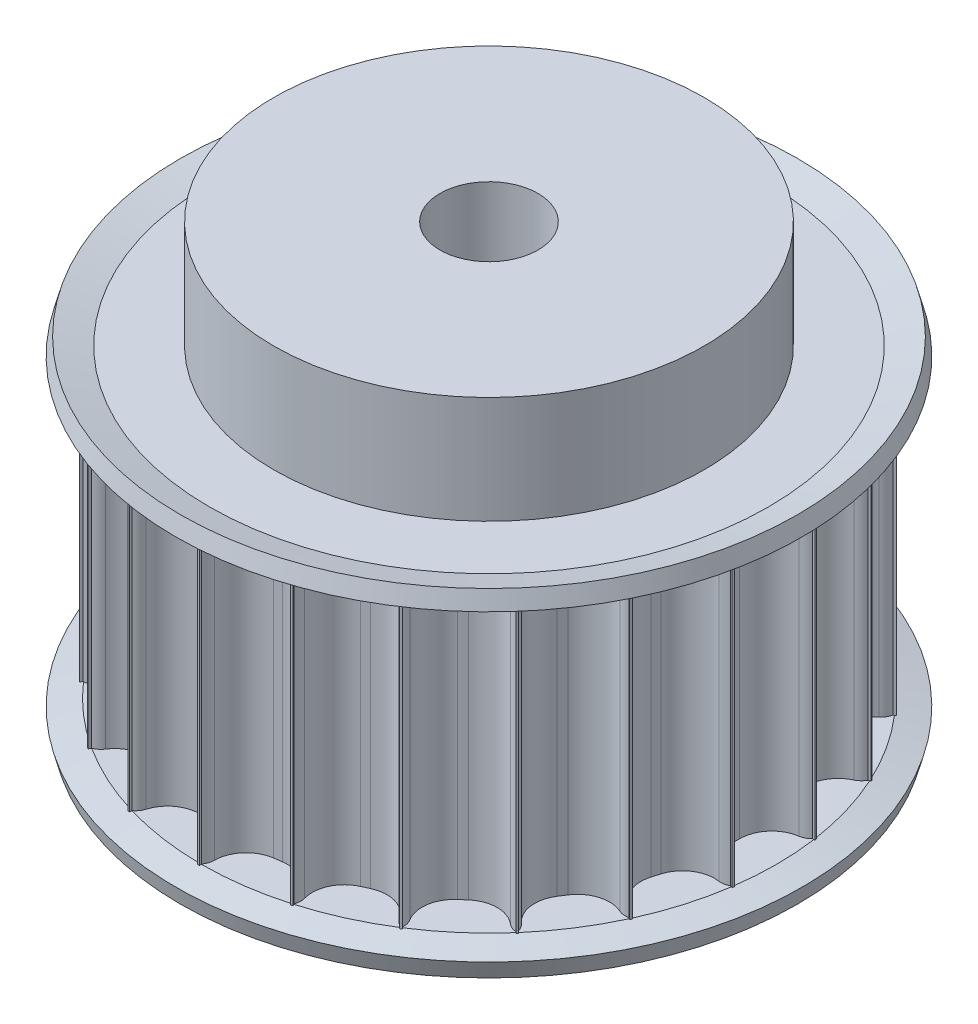
SolidWorks part; units mm, degrees
ref_plane "Front Plane" through (0, 0, 0) normal (0, 0, 1) x (1, 0, 0)
ref_plane "Top Plane" through (0, 0, 0) normal (0, 1, 0) x (1, 0, 0)
ref_plane "Right Plane" through (0, 0, 0) normal (1, 0, 0) x (0, 0, -1)
sketch "Sketch1" plane through (0, 0, 0) normal (0, 1, 0) x (1, 0, 0)
  circle A0 centre (0, 0) radius 6
  circle A1 centre (0, 0) radius 27
  dimension "D1" = 12
  dimension "D2" = 54
extrude "Boss-Extrude1" add sketch "Sketch1" along normal blind 27
sketch "Sketch2" plane through (0, 27, 0) normal (0, 1, 0) x (1, 0, 0)
  line L0 (0, 0) -> (31.3438, 0) construction
  line L1 (23.1111, 0.3611) -> (23.1111, -0.3611)
  line L2 (26.5, 3.75) -> (27.8859, 3.75)
  line L3 (27.8859, 3.75) -> (27.8859, -3.75)
  line L4 (27.8859, -3.75) -> (26.5, -3.75)
  line L5 (22.2766, -6.1647) -> (22.0732, -6.8576)
  line L6 (26.4831, -3.8678) -> (27.8128, -4.2583)
  line L7 (27.8128, -4.2583) -> (25.6998, -11.4545)
  line L8 (25.6998, -11.4545) -> (24.3701, -11.064)
  line L9 (19.6375, -12.191) -> (19.2471, -12.7986)
  line L10 (24.3206, -11.1723) -> (25.4865, -11.9215)
  line L11 (25.4865, -11.9215) -> (21.4317, -18.2309)
  line L12 (21.4317, -18.2309) -> (20.2658, -17.4817)
  line L13 (15.4074, -17.2297) -> (14.8617, -17.7026)
  line L14 (20.1879, -17.5716) -> (21.0954, -18.619)
  line L15 (21.0954, -18.619) -> (15.4273, -23.5305)
  line L16 (15.4273, -23.5305) -> (14.5197, -22.4831)
  line L17 (9.9291, -20.8726) -> (9.2722, -21.1726)
  line L18 (14.4196, -22.5474) -> (14.9953, -23.8081)
  line L19 (14.9953, -23.8081) -> (8.1731, -26.9237)
  line L20 (8.1731, -26.9237) -> (7.5974, -25.6631)
  line L21 (3.6465, -22.8245) -> (2.9316, -22.9272)
  line L22 (7.4832, -25.6966) -> (7.6804, -27.0683)
  line L23 (7.6804, -27.0683) -> (0.2567, -28.1357)
  line L24 (0.2567, -28.1357) -> (0.0595, -26.7639)
  line L25 (-2.9316, -22.9272) -> (-3.6465, -22.8245)
  line L26 (-0.0595, -26.7639) -> (-0.2567, -28.1357)
  line L27 (-0.2567, -28.1357) -> (-7.6804, -27.0683)
  line L28 (-7.6804, -27.0683) -> (-7.4832, -25.6966)
  line L29 (-9.2722, -21.1726) -> (-9.9291, -20.8726)
  line L30 (-7.5974, -25.6631) -> (-8.1731, -26.9237)
  line L31 (-8.1731, -26.9237) -> (-14.9953, -23.8081)
  line L32 (-14.9953, -23.8081) -> (-14.4196, -22.5474)
  line L33 (-14.8617, -17.7026) -> (-15.4074, -17.2297)
  line L34 (-14.5197, -22.4831) -> (-15.4273, -23.5305)
  line L35 (-15.4273, -23.5305) -> (-21.0954, -18.619)
  line L36 (-21.0954, -18.619) -> (-20.1879, -17.5716)
  line L37 (-19.2471, -12.7986) -> (-19.6375, -12.191)
  line L38 (-20.2658, -17.4817) -> (-21.4317, -18.2309)
  line L39 (-21.4317, -18.2309) -> (-25.4865, -11.9215)
  line L40 (-25.4865, -11.9215) -> (-24.3206, -11.1723)
  line L41 (-22.0732, -6.8576) -> (-22.2766, -6.1647)
  line L42 (-24.3701, -11.064) -> (-25.6998, -11.4545)
  line L43 (-25.6998, -11.4545) -> (-27.8128, -4.2583)
  line L44 (-27.8128, -4.2583) -> (-26.4831, -3.8678)
  line L45 (-23.1111, -0.3611) -> (-23.1111, 0.3611)
  line L46 (-26.5, -3.75) -> (-27.8859, -3.75)
  line L47 (-27.8859, -3.75) -> (-27.8859, 3.75)
  line L48 (-27.8859, 3.75) -> (-26.5, 3.75)
  line L49 (-22.2766, 6.1647) -> (-22.0732, 6.8576)
  line L50 (-26.4831, 3.8678) -> (-27.8128, 4.2583)
  line L51 (-27.8128, 4.2583) -> (-25.6998, 11.4545)
  line L52 (-25.6998, 11.4545) -> (-24.3701, 11.064)
  line L53 (-19.6375, 12.191) -> (-19.2471, 12.7986)
  line L54 (-24.3206, 11.1723) -> (-25.4865, 11.9215)
  line L55 (-25.4865, 11.9215) -> (-21.4317, 18.2309)
  line L56 (-21.4317, 18.2309) -> (-20.2658, 17.4817)
  line L57 (-15.4074, 17.2297) -> (-14.8617, 17.7026)
  line L58 (-20.1879, 17.5716) -> (-21.0954, 18.619)
  line L59 (-21.0954, 18.619) -> (-15.4273, 23.5305)
  line L60 (-15.4273, 23.5305) -> (-14.5197, 22.4831)
  line L61 (-9.9291, 20.8726) -> (-9.2722, 21.1726)
  line L62 (-14.4196, 22.5474) -> (-14.9953, 23.8081)
  line L63 (-14.9953, 23.8081) -> (-8.1731, 26.9237)
  line L64 (-8.1731, 26.9237) -> (-7.5974, 25.6631)
  line L65 (-3.6465, 22.8245) -> (-2.9316, 22.9272)
  line L66 (-7.4832, 25.6966) -> (-7.6804, 27.0683)
  line L67 (-7.6804, 27.0683) -> (-0.2567, 28.1357)
  line L68 (-0.2567, 28.1357) -> (-0.0595, 26.7639)
  line L69 (2.9316, 22.9272) -> (3.6465, 22.8245)
  line L70 (0.0595, 26.7639) -> (0.2567, 28.1357)
  line L71 (0.2567, 28.1357) -> (7.6804, 27.0683)
  line L72 (7.6804, 27.0683) -> (7.4832, 25.6966)
  line L73 (9.2722, 21.1726) -> (9.9291, 20.8726)
  line L74 (7.5974, 25.6631) -> (8.1731, 26.9237)
  line L75 (8.1731, 26.9237) -> (14.9953, 23.8081)
  line L76 (14.9953, 23.8081) -> (14.4196, 22.5474)
  line L77 (14.8617, 17.7026) -> (15.4074, 17.2297)
  line L78 (14.5197, 22.4831) -> (15.4273, 23.5305)
  line L79 (15.4273, 23.5305) -> (21.0954, 18.619)
  line L80 (21.0954, 18.619) -> (20.1879, 17.5716)
  line L81 (19.2471, 12.7986) -> (19.6375, 12.191)
  line L82 (20.2658, 17.4817) -> (21.4317, 18.2309)
  line L83 (21.4317, 18.2309) -> (25.4865, 11.9215)
  line L84 (25.4865, 11.9215) -> (24.3206, 11.1723)
  line L85 (22.0732, 6.8576) -> (22.2766, 6.1647)
  line L86 (24.3701, 11.064) -> (25.6998, 11.4545)
  line L87 (25.6998, 11.4545) -> (27.8128, 4.2583)
  line L88 (27.8128, 4.2583) -> (26.4831, 3.8678)
  arc A0 (26.5, 3.75) -> (25.6633, 3.3275) centre (25.4393, 4.8107) cw
  arc A1 (25.6633, -3.3275) -> (23.1111, -0.3611) centre (26.1111, -0.3611) cw
  arc A2 (25.6633, 3.3275) -> (23.1111, 0.3611) centre (26.1111, 0.3611) ccw
  arc A3 (26.5, -3.75) -> (25.6633, -3.3275) centre (25.4393, -4.8107) ccw
  arc A4 (26.4831, -3.8678) -> (25.5612, -4.0375) centre (25.7642, -2.5513) cw
  arc A5 (23.6863, -10.4229) -> (22.0732, -6.8576) centre (24.9517, -7.7028) cw
  arc A6 (25.5612, -4.0375) -> (22.2766, -6.1647) centre (25.1551, -7.0099) ccw
  arc A7 (24.3701, -11.064) -> (23.6863, -10.4229) centre (23.0535, -11.7829) ccw
  arc A8 (24.3206, -11.1723) -> (23.3883, -11.0754) centre (24.0018, -9.7066) cw
  arc A9 (19.7903, -16.6738) -> (19.2471, -12.7986) centre (21.7708, -14.4205) cw
  arc A10 (23.3883, -11.0754) -> (19.6375, -12.191) centre (22.1613, -13.813) ccw
  arc A11 (20.2658, -17.4817) -> (19.7903, -16.6738) centre (18.8001, -17.8005) ccw
  arc A12 (20.1879, -17.5716) -> (19.3206, -17.216) centre (20.2949, -16.0755) cw
  arc A13 (14.2911, -21.574) -> (14.8617, -17.7026) centre (16.8262, -19.9699) cw
  arc A14 (19.3206, -17.216) -> (15.4074, -17.2297) centre (17.372, -19.497) ccw
  arc A15 (14.5197, -22.4831) -> (14.2911, -21.574) centre (13.0236, -22.3761) ccw
  arc A16 (14.4196, -22.5474) -> (13.6877, -21.9618) centre (14.9438, -21.142) cw
  arc A17 (7.6341, -24.7264) -> (9.2722, -21.1726) centre (10.5185, -23.9015) cw
  arc A18 (13.6877, -21.9618) -> (9.9291, -20.8726) centre (11.1754, -23.6015) ccw
  arc A19 (7.5974, -25.6631) -> (7.6341, -24.7264) centre (6.192, -25.1389) ccw
  arc A20 (7.4832, -25.6966) -> (6.9459, -24.9285) centre (8.3821, -24.4958) cw
  arc A21 (0.3587, -25.8756) -> (2.9316, -22.9272) centre (3.3586, -25.8967) cw
  arc A22 (6.9459, -24.9285) -> (3.6465, -22.8245) centre (4.0734, -25.7939) ccw
  arc A23 (0.0595, -26.7639) -> (0.3587, -25.8756) centre (-1.1413, -25.865) ccw
  arc A24 (-0.0595, -26.7639) -> (-0.3587, -25.8756) centre (1.1413, -25.865) cw
  arc A25 (-6.9459, -24.9285) -> (-3.6465, -22.8245) centre (-4.0734, -25.7939) cw
  arc A26 (-0.3587, -25.8756) -> (-2.9316, -22.9272) centre (-3.3586, -25.8967) ccw
  arc A27 (-7.4832, -25.6966) -> (-6.9459, -24.9285) centre (-8.3821, -24.4958) ccw
  arc A28 (-7.5974, -25.6631) -> (-7.6341, -24.7264) centre (-6.192, -25.1389) cw
  arc A29 (-13.6877, -21.9618) -> (-9.9291, -20.8726) centre (-11.1754, -23.6015) cw
  arc A30 (-7.6341, -24.7264) -> (-9.2722, -21.1726) centre (-10.5185, -23.9015) ccw
  arc A31 (-14.4196, -22.5474) -> (-13.6877, -21.9618) centre (-14.9438, -21.142) ccw
  arc A32 (-14.5197, -22.4831) -> (-14.2911, -21.574) centre (-13.0236, -22.3761) cw
  arc A33 (-19.3206, -17.216) -> (-15.4074, -17.2297) centre (-17.372, -19.497) cw
  arc A34 (-14.2911, -21.574) -> (-14.8617, -17.7026) centre (-16.8262, -19.9699) ccw
  arc A35 (-20.1879, -17.5716) -> (-19.3206, -17.216) centre (-20.2949, -16.0755) ccw
  arc A36 (-20.2658, -17.4817) -> (-19.7903, -16.6738) centre (-18.8001, -17.8005) cw
  arc A37 (-23.3883, -11.0754) -> (-19.6375, -12.191) centre (-22.1613, -13.813) cw
  arc A38 (-19.7903, -16.6738) -> (-19.2471, -12.7986) centre (-21.7708, -14.4205) ccw
  arc A39 (-24.3206, -11.1723) -> (-23.3883, -11.0754) centre (-24.0018, -9.7066) ccw
  arc A40 (-24.3701, -11.064) -> (-23.6863, -10.4229) centre (-23.0535, -11.7829) cw
  arc A41 (-25.5612, -4.0375) -> (-22.2766, -6.1647) centre (-25.1551, -7.0099) cw
  arc A42 (-23.6863, -10.4229) -> (-22.0732, -6.8576) centre (-24.9517, -7.7028) ccw
  arc A43 (-26.4831, -3.8678) -> (-25.5612, -4.0375) centre (-25.7642, -2.5513) ccw
  arc A44 (-26.5, -3.75) -> (-25.6633, -3.3275) centre (-25.4393, -4.8107) cw
  arc A45 (-25.6633, 3.3275) -> (-23.1111, 0.3611) centre (-26.1111, 0.3611) cw
  arc A46 (-25.6633, -3.3275) -> (-23.1111, -0.3611) centre (-26.1111, -0.3611) ccw
  arc A47 (-26.5, 3.75) -> (-25.6633, 3.3275) centre (-25.4393, 4.8107) ccw
  arc A48 (-26.4831, 3.8678) -> (-25.5612, 4.0375) centre (-25.7642, 2.5513) cw
  arc A49 (-23.6863, 10.4229) -> (-22.0732, 6.8576) centre (-24.9517, 7.7028) cw
  arc A50 (-25.5612, 4.0375) -> (-22.2766, 6.1647) centre (-25.1551, 7.0099) ccw
  arc A51 (-24.3701, 11.064) -> (-23.6863, 10.4229) centre (-23.0535, 11.7829) ccw
  arc A52 (-24.3206, 11.1723) -> (-23.3883, 11.0754) centre (-24.0018, 9.7066) cw
  arc A53 (-19.7903, 16.6738) -> (-19.2471, 12.7986) centre (-21.7708, 14.4205) cw
  arc A54 (-23.3883, 11.0754) -> (-19.6375, 12.191) centre (-22.1613, 13.813) ccw
  arc A55 (-20.2658, 17.4817) -> (-19.7903, 16.6738) centre (-18.8001, 17.8005) ccw
  arc A56 (-20.1879, 17.5716) -> (-19.3206, 17.216) centre (-20.2949, 16.0755) cw
  arc A57 (-14.2911, 21.574) -> (-14.8617, 17.7026) centre (-16.8262, 19.9699) cw
  arc A58 (-19.3206, 17.216) -> (-15.4074, 17.2297) centre (-17.372, 19.497) ccw
  arc A59 (-14.5197, 22.4831) -> (-14.2911, 21.574) centre (-13.0236, 22.3761) ccw
  arc A60 (-14.4196, 22.5474) -> (-13.6877, 21.9618) centre (-14.9438, 21.142) cw
  arc A61 (-7.6341, 24.7264) -> (-9.2722, 21.1726) centre (-10.5185, 23.9015) cw
  arc A62 (-13.6877, 21.9618) -> (-9.9291, 20.8726) centre (-11.1754, 23.6015) ccw
  arc A63 (-7.5974, 25.6631) -> (-7.6341, 24.7264) centre (-6.192, 25.1389) ccw
  arc A64 (-7.4832, 25.6966) -> (-6.9459, 24.9285) centre (-8.3821, 24.4958) cw
  arc A65 (-0.3587, 25.8756) -> (-2.9316, 22.9272) centre (-3.3586, 25.8967) cw
  arc A66 (-6.9459, 24.9285) -> (-3.6465, 22.8245) centre (-4.0734, 25.7939) ccw
  arc A67 (-0.0595, 26.7639) -> (-0.3587, 25.8756) centre (1.1413, 25.865) ccw
  arc A68 (0.0595, 26.7639) -> (0.3587, 25.8756) centre (-1.1413, 25.865) cw
  arc A69 (6.9459, 24.9285) -> (3.6465, 22.8245) centre (4.0734, 25.7939) cw
  arc A70 (0.3587, 25.8756) -> (2.9316, 22.9272) centre (3.3586, 25.8967) ccw
  arc A71 (7.4832, 25.6966) -> (6.9459, 24.9285) centre (8.3821, 24.4958) ccw
  arc A72 (7.5974, 25.6631) -> (7.6341, 24.7264) centre (6.192, 25.1389) cw
  arc A73 (13.6877, 21.9618) -> (9.9291, 20.8726) centre (11.1754, 23.6015) cw
  arc A74 (7.6341, 24.7264) -> (9.2722, 21.1726) centre (10.5185, 23.9015) ccw
  arc A75 (14.4196, 22.5474) -> (13.6877, 21.9618) centre (14.9438, 21.142) ccw
  arc A76 (14.5197, 22.4831) -> (14.2911, 21.574) centre (13.0236, 22.3761) cw
  arc A77 (19.3206, 17.216) -> (15.4074, 17.2297) centre (17.372, 19.497) cw
  arc A78 (14.2911, 21.574) -> (14.8617, 17.7026) centre (16.8262, 19.9699) ccw
  arc A79 (20.1879, 17.5716) -> (19.3206, 17.216) centre (20.2949, 16.0755) ccw
  arc A80 (20.2658, 17.4817) -> (19.7903, 16.6738) centre (18.8001, 17.8005) cw
  arc A81 (23.3883, 11.0754) -> (19.6375, 12.191) centre (22.1613, 13.813) cw
  arc A82 (19.7903, 16.6738) -> (19.2471, 12.7986) centre (21.7708, 14.4205) ccw
  arc A83 (24.3206, 11.1723) -> (23.3883, 11.0754) centre (24.0018, 9.7066) ccw
  arc A84 (24.3701, 11.064) -> (23.6863, 10.4229) centre (23.0535, 11.7829) cw
  arc A85 (25.5612, 4.0375) -> (22.2766, 6.1647) centre (25.1551, 7.0099) cw
  arc A86 (23.6863, 10.4229) -> (22.0732, 6.8576) centre (24.9517, 7.7028) ccw
  arc A87 (26.4831, 3.8678) -> (25.5612, 4.0375) centre (25.7642, 2.5513) ccw
  point P270 (0, 0)
  dimension "D1" = 3
  dimension "D2" = 1.5
  dimension "D4" = 7.5
  dimension "D3" = 26.5
  dimension "D5" = 0.7222
  dimension "D6" = 22
extrude "Cut-Extrude1" cut sketch "Sketch2" against normal blind 27 contours L51 L52 A51 A49 L49 A50 A48 L50
sketch "Sketch3" plane through (0, 0, 0) normal (0, 0, 1) x (1, 0, 0)
  line L0 (0.0934, 0) -> (0.0934, 31.0136) construction
  line L1 (-25.9711, -1.5) -> (-19.9811, -1.5)
  line L2 (-26.7117, 27) -> (-29.1072, 27.6419)
  line L3 (-4.4811, 27) -> (-26.7117, 27)
  line L4 (-29.1072, 27.6419) -> (-28.6826, 29.2265)
  line L6 (-19.9811, 28.5) -> (-19.9811, 38.5)
  line L7 (-19.9811, 38.5) -> (-4.4811, 38.5)
  line L8 (-4.4811, 38.5) -> (-4.4811, 27)
  line L14 (-26.7117, 13.5) -> (-0.7784, 13.5) construction
  line L15 (-26.7117, 0) -> (-26.7117, 27) construction
  line L16 (-28.6826, 29.2265) -> (-25.9711, 28.5)
  line L17 (-25.9711, 28.5) -> (-19.9811, 28.5)
  line L18 (-28.6826, -2.2265) -> (-25.9711, -1.5)
  line L19 (-29.1072, -0.6419) -> (-28.6826, -2.2265)
  line L20 (-4.4811, 0) -> (-26.7117, 0)
  line L21 (-26.7117, 0) -> (-29.1072, -0.6419)
  line L22 (0.0934, 0) -> (-4.4811, 0)
  line L23 (-19.9811, -1.5) -> (0.0934, -1.5)
  line L24 (0.0934, -1.5) -> (0.0934, 0)
  dimension "D1" = 2.48
  dimension "D2" = 5.99
  dimension "D3" = 1.5
  dimension "D4" = 165
  dimension "D5" = 15.5
  dimension "D6" = 10
  dimension "D7" = 4.5745
revolve "Revolve1" add sketch "Sketch3" angle 360 about L0
sketch "Sketch4" plane through (0, 38.5, 0) normal (0, 1, 0) x (1, 0, 0)
  circle A0 centre (0.0934, 0) radius 4.5745 construction
  circle A1 centre (0.0934, 0) radius 4.5745
extrude "Cut-Extrude2" cut sketch "Sketch4" against normal blind 51
